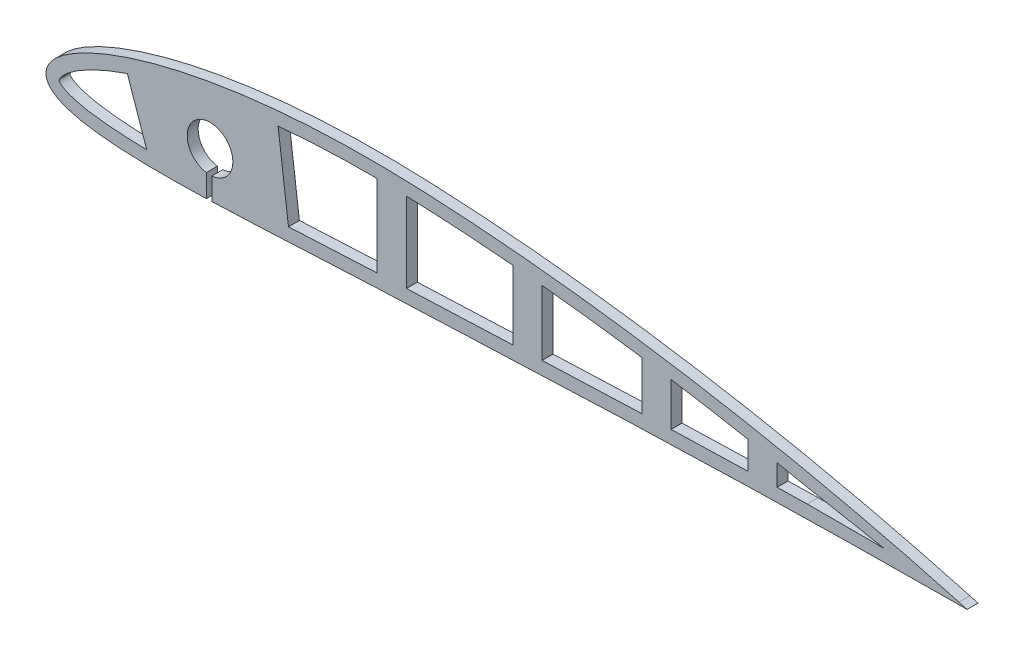
SolidWorks part; units mm, degrees
ref_plane "Front Plane" through (0, 0, 0) normal (0, 0, 1) x (1, 0, 0)
ref_plane "Top Plane" through (0, 0, 0) normal (0, 1, 0) x (1, 0, 0)
ref_plane "Right Plane" through (0, 0, 0) normal (1, 0, 0) x (0, 0, -1)
sketch "Sketch1" plane through (0, 0, 1594.6656) normal (0, 0, 1) x (1, 0, 0)
  line L2 (571.5128, 751.4609) -> (569.2886, 752.0854)
  line L3 (569.2051, 751.4609) -> (571.5128, 751.4609)
  line L4 (569.2051, 751.4609) -> (571.5128, 751.4609) construction
  spline S1 degree 3 poles (569.2886, 752.0854) (569.2078, 752.1078) (568.8853, 752.1974) (568.1605, 752.3973) (566.9556, 752.729) (565.2743, 753.1866) (562.1009, 754.0411) (558.3152, 755.0358) (553.9297, 756.1554) (549.9887, 757.1383) (545.6315, 758.1963) (540.8742, 759.3181) (535.7338, 760.4908) (530.2297, 761.7033) (524.3818, 762.9407) (518.2126, 764.1926) (511.7451, 765.4444) (505.0038, 766.684) (498.015, 767.8998) (490.8053, 769.0779) (483.403, 770.2081) (475.8368, 771.278) (468.1369, 772.277) (460.3337, 773.194) (452.4584, 774.0199) (444.5428, 774.7452) (436.619, 775.3619) (428.7194, 775.8607) (420.844, 776.2435) (413.0149, 776.4797) (405.2648, 776.5088) (397.6615, 776.3435) (390.2476, 775.9856) (383.0567, 775.4408) (376.1212, 774.7193) (369.4725, 773.8315) (363.1401, 772.7913) (357.1519, 771.6135) (351.5339, 770.3153) (346.3098, 768.915) (341.501, 767.4314) (337.1267, 765.8839) (333.2027, 764.2928) (329.7432, 762.6763) (326.7587, 761.0528) (324.2574, 759.4384) (322.2434, 757.8466) (320.7178, 756.2854) (319.6806, 754.7538) (319.1458, 753.2369) (319.159, 751.7555) (319.7158, 750.3843) (320.7825, 749.1883) (322.304, 748.1611) (324.27, 747.2776) (326.6763, 746.5255) (329.5165, 745.9001) (332.7801, 745.3971) (336.4542, 745.0122) (340.5236, 744.7407) (344.9719, 744.5753) (349.7816, 744.5103) (354.9341, 744.5357) (360.4104, 744.6431) (366.1905, 744.8216) (372.2543, 745.0601) (378.5807, 745.3457) (385.1483, 745.6665) (391.935, 746.0089) (398.9183, 746.3597) (406.0748, 746.7054) (413.3888, 747.0362) (420.8688, 747.3274) (428.4856, 747.624) (436.2018, 747.9413) (443.9555, 748.2639) (451.7173, 748.586) (459.4574, 748.9018) (467.146, 749.2057) (474.7531, 749.4935) (482.249, 749.7621) (489.6041, 750.0086) (496.7891, 750.2326) (503.7754, 750.4327) (510.5347, 750.6093) (517.0396, 750.7629) (523.2634, 750.8957) (529.1806, 751.0078) (534.7667, 751.1025) (539.9984, 751.1811) (544.8539, 751.2454) (549.3124, 751.2978) (553.3551, 751.3399) (556.9645, 751.3737) (560.1251, 751.3998) (562.8233, 751.4199) (565.0473, 751.4355) (566.7873, 751.4467) (568.0357, 751.4543) (568.7869, 751.4584) (569.1214, 751.4604) (569.2051, 751.4609) knots 0 0 0 0 0.000491 0.001962 0.004406 0.007815 0.012174 0.023667 0.030754 0.0387 0.04747 0.057032 0.067345 0.07837 0.090062 0.102376 0.115262 0.128669 0.142545 0.156835 0.171482 0.186429 0.201617 0.216985 0.232474 0.248023 0.263569 0.279051 0.29441 0.309776 0.324951 0.339825 0.354342 0.368446 0.382083 0.395202 0.407751 0.419686 0.430962 0.441537 0.451377 0.460447 0.468723 0.476183 0.482815 0.488619 0.49361 0.49783 0.501365 0.504372 0.507113 0.509853 0.512855 0.516368 0.52054 0.525445 0.531118 0.537568 0.544788 0.552762 0.561466 0.570873 0.58095 0.591662 0.602972 0.614841 0.627227 0.640086 0.653377 0.667052 0.681064 0.695367 0.70996 0.724934 0.74004 0.75522 0.770415 0.785568 0.800619 0.81551 0.830182 0.844577 0.858639 0.872311 0.885538 0.898266 0.910444 0.922022 0.932951 0.943187 0.952686 0.961409 0.969318 0.97638 0.982563 0.987842 0.992193 0.995598 0.99804 0.99951 1 1 1 1
  dimension "D1" = 2.2242
  dimension "D2" = 2.3077
  dimension "D3" = 0.6245
extrude "Boss-Extrude1" add sketch "Sketch1" along normal blind 3
sketch "Sketch2" plane through (0, 0, 1597.6656) normal (0, 0, 1) x (1, 0, 0)
  line L1 (527.0417, 758.6959) -> (548.7945, 754.58)
  line L2 (548.7945, 754.58) -> (527.7227, 754.58)
  spline S0 degree 3 poles (1474.0155, 3610.6619) (637.218, 726.0279) (603.832, 742.5568) (568.1605, 752.3973) (566.9556, 752.729) (565.2743, 753.1866) (562.1009, 754.0411) (558.3152, 755.0358) (553.9297, 756.1554) (549.9887, 757.1383) (545.6315, 758.1963) (540.8742, 759.3181) (535.7338, 760.4908) (530.2297, 761.7033) (524.3818, 762.9407) (518.2126, 764.1926) (511.7451, 765.4444) (505.0038, 766.684) (498.015, 767.8998) (490.8053, 769.0779) (483.403, 770.2081) (475.8368, 771.278) (468.1369, 772.277) (460.3337, 773.194) (452.4584, 774.0199) (444.5428, 774.7452) (436.619, 775.3619) (428.7194, 775.8607) (420.844, 776.2435) (413.0149, 776.4797) (405.2648, 776.5088) (397.6615, 776.3435) (390.2476, 775.9856) (383.0567, 775.4408) (376.1212, 774.7193) (369.4725, 773.8315) (363.1401, 772.7913) (357.1519, 771.6135) (351.5339, 770.3153) (346.3098, 768.915) (341.501, 767.4314) (337.1267, 765.8839) (333.2027, 764.2928) (329.7432, 762.6763) (326.7587, 761.0528) (324.2574, 759.4384) (322.2434, 757.8466) (320.7178, 756.2854) (319.6806, 754.7538) (319.1458, 753.2369) (319.159, 751.7555) (319.7158, 750.3843) (320.7825, 749.1883) (322.304, 748.1611) (324.27, 747.2776) (326.6763, 746.5255) (329.5165, 745.9001) (332.7801, 745.3971) (336.4542, 745.0122) (340.5236, 744.7407) (344.9719, 744.5753) (349.7816, 744.5103) (354.9341, 744.5357) (360.4104, 744.6431) (366.1905, 744.8216) (372.2543, 745.0601) (378.5807, 745.3457) (385.1483, 745.6665) (391.935, 746.0089) (398.9183, 746.3597) (406.0748, 746.7054) (413.3888, 747.0362) (420.8688, 747.3274) (428.4856, 747.624) (436.2018, 747.9413) (443.9555, 748.2639) (451.7173, 748.586) (459.4574, 748.9018) (467.146, 749.2057) (474.7531, 749.4935) (482.249, 749.7621) (489.6041, 750.0086) (496.7891, 750.2326) (503.7754, 750.4327) (510.5347, 750.6093) (517.0396, 750.7629) (523.2634, 750.8957) (529.1806, 751.0078) (534.7667, 751.1025) (539.9984, 751.1811) (544.8539, 751.2454) (549.3124, 751.2978) (553.3551, 751.3399) (556.9645, 751.3737) (560.1251, 751.3998) (562.8233, 751.4199) (565.0473, 751.4355) (566.7873, 751.4467) (568.0357, 751.4543) (620.0518, 751.7355) (671.6226, 756.9637) (740.364, -2240.9775) knots -0.212459 -0.212459 -0.212459 -0.212459 0.000491 0.001962 0.004406 0.007815 0.012174 0.023667 0.030754 0.0387 0.04747 0.057032 0.067345 0.07837 0.090062 0.102376 0.115262 0.128669 0.142545 0.156835 0.171482 0.186429 0.201617 0.216985 0.232474 0.248023 0.263569 0.279051 0.29441 0.309776 0.324951 0.339825 0.354342 0.368446 0.382083 0.395202 0.407751 0.419686 0.430962 0.441537 0.451377 0.460447 0.468723 0.476183 0.482815 0.488619 0.49361 0.49783 0.501365 0.504372 0.507113 0.509853 0.512855 0.516368 0.52054 0.525445 0.531118 0.537568 0.544788 0.552762 0.561466 0.570873 0.58095 0.591662 0.602972 0.614841 0.627227 0.640086 0.653377 0.667052 0.681064 0.695367 0.70996 0.724934 0.74004 0.75522 0.770415 0.785568 0.800619 0.81551 0.830182 0.844577 0.858639 0.872311 0.885538 0.898266 0.910444 0.922022 0.932951 0.943187 0.952686 0.961409 0.969318 0.97638 0.982563 0.987842 0.992193 0.995598 0.99804 0.99951 1.300448 1.300448 1.300448 1.300448 only from (569.2886, 752.0854) to (569.2051, 751.4609) construction
  spline S1 degree 3 poles (527.7891, 762.2175) (526.6879, 762.4512) (523.5298, 763.1136) (518.2126, 764.1926) (511.7451, 765.4444) (505.0038, 766.684) (498.015, 767.8998) (490.8053, 769.0779) (483.403, 770.2081) (475.8368, 771.278) (468.1369, 772.277) (460.3337, 773.194) (452.4584, 774.0199) (444.5428, 774.7452) (436.619, 775.3619) (428.7194, 775.8607) (420.844, 776.2435) (413.0149, 776.4797) (405.2648, 776.5088) (397.6615, 776.3435) (390.2476, 775.9856) (383.0567, 775.4408) (376.1212, 774.7193) (369.4725, 773.8315) (363.1401, 772.7913) (357.1519, 771.6135) (351.5339, 770.3153) (346.3098, 768.915) (341.501, 767.4314) (337.1267, 765.8839) (333.2027, 764.2928) (329.7432, 762.6763) (326.7587, 761.0528) (324.2574, 759.4384) (322.2434, 757.8466) (320.7178, 756.2854) (319.6806, 754.7538) (319.1458, 753.2369) (319.159, 751.7555) (319.7158, 750.3843) (320.7825, 749.1883) (322.304, 748.1611) (324.27, 747.2776) (326.6763, 746.5255) (329.5165, 745.9001) (332.7801, 745.3971) (336.4542, 745.0122) (340.5236, 744.7407) (344.9719, 744.5753) (349.7816, 744.5103) (354.9341, 744.5357) (360.4104, 744.6431) (366.1905, 744.8216) (372.2543, 745.0601) (378.5807, 745.3457) (385.1483, 745.6665) (391.935, 746.0089) (398.9183, 746.3597) (406.0748, 746.7054) (413.3888, 747.0362) (420.8688, 747.3274) (428.4856, 747.624) (436.2018, 747.9413) (443.9555, 748.2639) (451.7173, 748.586) (459.4574, 748.9018) (467.146, 749.2057) (474.7531, 749.4935) (482.249, 749.7621) (489.6041, 750.0086) (496.7891, 750.2326) (503.7754, 750.4327) (510.5347, 750.6093) (517.0396, 750.7629) (522.7627, 750.8851) (526.3146, 750.9534) (527.7891, 750.9806) knots 0.083465 0.083465 0.083465 0.083465 0.090062 0.102376 0.115262 0.128669 0.142545 0.156835 0.171482 0.186429 0.201617 0.216985 0.232474 0.248023 0.263569 0.279051 0.29441 0.309776 0.324951 0.339825 0.354342 0.368446 0.382083 0.395202 0.407751 0.419686 0.430962 0.441537 0.451377 0.460447 0.468723 0.476183 0.482815 0.488619 0.49361 0.49783 0.501365 0.504372 0.507113 0.509853 0.512855 0.516368 0.52054 0.525445 0.531118 0.537568 0.544788 0.552762 0.561466 0.570873 0.58095 0.591662 0.602972 0.614841 0.627227 0.640086 0.653377 0.667052 0.681064 0.695367 0.70996 0.724934 0.74004 0.75522 0.770415 0.785568 0.800619 0.81551 0.830182 0.844577 0.858639 0.872311 0.885538 0.898266 0.910444 0.919086 0.919086 0.919086 0.919086
  spline S2 degree 1 poles (527.0417, 758.6959) (527.7227, 754.58) knots 0 0 1 1 construction
  spline S3 degree 3 poles (527.0417, 758.6959) (518.3683, 760.5366) (500.951, 763.8997) (474.6628, 767.966) (452.6455, 770.4843) (434.9947, 771.8985) (421.7276, 772.6482) (408.5168, 772.9897) (395.3109, 772.7186) (382.1513, 771.8268) (369.0794, 770.2343) (358.3167, 768.246) (349.847, 766.1775) (343.5957, 764.3541) (338.5068, 762.5685) (334.5578, 760.9433) (331.6806, 759.611) (328.9259, 758.1483) (326.7893, 756.8009) (325.2575, 755.6451) (324.2356, 754.7445) (323.4068, 753.8367) (322.9706, 753.1632) (322.806, 752.7516) (322.772, 752.5946) (322.7737, 752.4904) (322.7757, 752.4752) (322.8114, 752.3798) (322.9212, 752.2073) (323.3921, 751.7489) (324.3594, 751.1809) (325.9668, 750.4938) (328.321, 749.8167) (331.3568, 749.2376) (334.5038, 748.823) (337.7102, 748.531) (342.0359, 748.266) (347.4998, 748.1146) (354.1019, 748.1186) (360.7281, 748.2487) (369.5843, 748.5376) (380.6814, 749.0417) (394.0264, 749.7204) (407.3902, 750.3878) (420.7874, 750.9298) (434.1212, 751.4525) (451.9322, 752.2032) (474.2053, 753.1053) (500.9583, 753.9965) (518.8009, 754.4154) (527.7227, 754.58) knots 0.083465 0.083465 0.083465 0.083465 0.135691 0.187918 0.240144 0.266257 0.29237 0.318483 0.344597 0.37071 0.396823 0.422936 0.435993 0.449049 0.462106 0.468634 0.475163 0.481691 0.488219 0.491483 0.494747 0.498012 0.501276 0.502908 0.50454 0.506172 0.507804 0.509436 0.511068 0.514332 0.517596 0.520861 0.527389 0.533917 0.540445 0.546974 0.553502 0.566559 0.579615 0.592672 0.605728 0.631842 0.657955 0.684068 0.710181 0.736294 0.762407 0.814634 0.86686 0.919086 0.919086 0.919086 0.919086
  dimension "D2" = 20.4106
  dimension "D3" = 41.416
  dimension "D1" = 3.6
extrude "Cut-Extrude1" cut sketch "Sketch2" against normal blind 10 contours L1 S3 L2
sketch "Sketch3" plane through (0, 0, 1597.6656) normal (0, 0, 1) x (1, 0, 0)
  line L0 (341.459, 763.5841) -> (346.7502, 748.157)
  line L1 (349.1123, 765.9288) -> (355.2092, 748.1525)
  line L2 (374.8049, 770.8978) -> (377.5857, 748.907)
  line L3 (382.7589, 771.7654) -> (385.6004, 749.2948)
  line L4 (409.9199, 772.8805) -> (409.9199, 750.4788)
  line L5 (417.9199, 772.7198) -> (417.9199, 750.8122)
  line L6 (447.0835, 770.8916) -> (447.0835, 751.9966)
  line L7 (455.0835, 770.1204) -> (455.0835, 752.3265)
  line L8 (482.4324, 766.6979) -> (482.4324, 753.3674)
  line L9 (490.4324, 765.4793) -> (490.4324, 753.6341)
  line L10 (511.4605, 761.8237) -> (511.4605, 754.2305)
  line L11 (519.4605, 760.2624) -> (519.4605, 754.4148)
  spline S0 degree 3 poles (-11417.7675, -27.8816) (2199.8699, -1917.6866) (1537.1945, 603.6136) (474.6628, 767.966) (452.6455, 770.4843) (434.9947, 771.8985) (421.7276, 772.6482) (408.5168, 772.9897) (395.3109, 772.7186) (382.1513, 771.8268) (369.0794, 770.2343) (358.3167, 768.246) (349.847, 766.1775) (343.5957, 764.3541) (338.5068, 762.5685) (334.5578, 760.9433) (331.6806, 759.611) (328.9259, 758.1483) (326.7893, 756.8009) (325.2575, 755.6451) (324.2356, 754.7445) (323.4068, 753.8367) (322.9706, 753.1632) (322.806, 752.7516) (322.772, 752.5946) (322.7737, 752.4904) (322.7757, 752.4752) (322.8114, 752.3798) (322.9212, 752.2073) (323.3921, 751.7489) (324.3594, 751.1809) (325.9668, 750.4938) (328.321, 749.8167) (331.3568, 749.2376) (334.5038, 748.823) (337.7102, 748.531) (342.0359, 748.266) (347.4998, 748.1146) (354.1019, 748.1186) (360.7281, 748.2487) (369.5843, 748.5376) (380.6814, 749.0417) (394.0264, 749.7204) (407.3902, 750.3878) (420.7874, 750.9298) (434.1212, 751.4525) (451.9322, 752.2032) (474.2053, 753.1053) (2123.5149, 808.0517) (3825.2982, -620.0168) (-2516.8948, -10259.5003) knots -6.092595 -6.092595 -6.092595 -6.092595 0.135691 0.187918 0.240144 0.266257 0.29237 0.318483 0.344597 0.37071 0.396823 0.422936 0.435993 0.449049 0.462106 0.468634 0.475163 0.481691 0.488219 0.491483 0.494747 0.498012 0.501276 0.502908 0.50454 0.506172 0.507804 0.509436 0.511068 0.514332 0.517596 0.520861 0.527389 0.533917 0.540445 0.546974 0.553502 0.566559 0.579615 0.592672 0.605728 0.631842 0.657955 0.684068 0.710181 0.736294 0.762407 0.814634 0.86686 10.421587 10.421587 10.421587 10.421587 only from (527.0417, 758.6959) to (527.7227, 754.58) construction
  spline S1 degree 3 poles (519.4605, 760.2624) (516.7968, 760.7979) (514.1301, 761.3184) (511.4605, 761.8237) knots 0.098664 0.098664 0.098664 0.098664 0.114666 0.114666 0.114666 0.114666
  spline S2 degree 3 poles (346.7502, 748.157) (347.0025, 748.1528) (349.4472, 748.1158) (352.2682, 748.1175) (354.8414, 748.1477) (355.2092, 748.1525) knots 0.565055 0.565055 0.565055 0.565055 0.566559 0.579615 0.581793 0.581793 0.581793 0.581793
  spline S3 degree 3 poles (349.1123, 765.9288) (347.2661, 765.4238) (344.7027, 764.6672) (342.1758, 763.8299) (341.459, 763.5841) knots 0.437551 0.437551 0.437551 0.437551 0.449049 0.453635 0.453635 0.453635 0.453635
  spline S4 degree 3 poles (377.5857, 748.907) (378.6189, 748.9551) (381.2895, 749.082) (383.9617, 749.2133) (385.6004, 749.2948) knots 0.625767 0.625767 0.625767 0.625767 0.631842 0.641464 0.641464 0.641464 0.641464
  spline S5 degree 3 poles (382.7589, 771.7654) (382.5612, 771.7472) (379.9042, 771.4988) (377.2526, 771.2073) (374.8049, 770.8978) knots 0.369529 0.369529 0.369529 0.369529 0.37071 0.385397 0.385397 0.385397 0.385397
  spline S6 degree 3 poles (409.9199, 750.4788) (412.5868, 750.5949) (415.2546, 750.7048) (417.9199, 750.8122) knots 0.688993 0.688993 0.688993 0.688993 0.704602 0.704602 0.704602 0.704602
  spline S7 degree 3 poles (417.9199, 772.7198) (415.2513, 772.8044) (412.5853, 772.8605) (409.9199, 772.8805) knots 0.299904 0.299904 0.299904 0.299904 0.315711 0.315711 0.315711 0.315711
  spline S8 degree 3 poles (447.0835, 751.9966) (447.2157, 752.0021) (449.8821, 752.1131) (452.5488, 752.2232) (455.0835, 752.3265) knots 0.761632 0.761632 0.761632 0.761632 0.762407 0.777268 0.777268 0.777268 0.777268
  spline S9 degree 3 poles (455.0835, 770.1204) (452.7998, 770.356) (450.1333, 770.6159) (447.4656, 770.8574) (447.0835, 770.8916) knots 0.22661 0.22661 0.22661 0.22661 0.240144 0.242406 0.242406 0.242406 0.242406
  spline S10 degree 3 poles (482.4324, 753.3674) (485.0988, 753.4596) (487.7654, 753.5486) (490.4324, 753.6341) knots 0.830692 0.830692 0.830692 0.830692 0.846311 0.846311 0.846311 0.846311
  spline S11 degree 3 poles (490.4324, 765.4793) (487.768, 765.9011) (485.1013, 766.3074) (482.4324, 766.6979) knots 0.156574 0.156574 0.156574 0.156574 0.172465 0.172465 0.172465 0.172465
  spline S12 degree 3 poles (511.4605, 754.2305) (514.127, 754.2959) (516.7937, 754.3573) (519.4605, 754.4148) knots 0.887353 0.887353 0.887353 0.887353 0.902964 0.902964 0.902964 0.902964
  spline M8 degree 3 poles (527.7227, 754.58) (518.8009, 754.4154) (500.9583, 753.9965) (474.2053, 753.1053) (451.9322, 752.2032) (434.1212, 751.4525) (420.7874, 750.9298) (407.3902, 750.3878) (394.0264, 749.7204) (380.6814, 749.0417) (369.5843, 748.5376) (360.7281, 748.2487) (354.1019, 748.1186) (347.4998, 748.1146) (342.0359, 748.266) (337.7102, 748.531) (334.5038, 748.823) (331.3568, 749.2376) (328.321, 749.8167) (325.9668, 750.4938) (324.3594, 751.1809) (323.3921, 751.7489) (322.9212, 752.2073) (322.8114, 752.3798) (322.7757, 752.4752) (322.7737, 752.4904) (322.772, 752.5946) (322.806, 752.7516) (322.9706, 753.1632) (323.4068, 753.8367) (324.2356, 754.7445) (325.2575, 755.6451) (326.7893, 756.8009) (328.9259, 758.1483) (331.6806, 759.611) (334.5578, 760.9433) (338.5068, 762.5685) (343.5957, 764.3541) (349.847, 766.1775) (358.3167, 768.246) (369.0794, 770.2343) (382.1513, 771.8268) (395.3109, 772.7186) (408.5168, 772.9897) (421.7276, 772.6482) (434.9947, 771.8985) (452.6455, 770.4843) (474.6628, 767.966) (500.951, 763.8997) (518.3683, 760.5366) (527.0417, 758.6959) knots 0.083465 0.083465 0.083465 0.083465 0.135691 0.187918 0.240144 0.266257 0.29237 0.318483 0.344597 0.37071 0.396823 0.40988 0.422936 0.435993 0.449049 0.455578 0.462106 0.468634 0.475163 0.481691 0.484955 0.488219 0.491483 0.493115 0.494747 0.496379 0.498012 0.499644 0.501276 0.50454 0.507804 0.511068 0.514332 0.520861 0.527389 0.533917 0.540445 0.553502 0.566559 0.579615 0.605728 0.631842 0.657955 0.684068 0.710181 0.736294 0.762407 0.814634 0.86686 0.919086 0.919086 0.919086 0.919086
  dimension "D1" = 8
  dimension "D2" = 8
  dimension "D3" = 8
  dimension "D4" = 8
  dimension "D5" = 8
  dimension "D6" = 8
  dimension "D7" = 49.7446
  dimension "D8" = 78.7727
  dimension "D9" = 114.1216
  dimension "D10" = 151.2852
  dimension "D11" = 183.6047
  dimension "D12" = 186.4462
  dimension "D13" = 213.9958
  dimension "D14" = 220.0927
extrude "Boss-Extrude2" add sketch "Sketch3" against normal blind 3 contours L3 L2 M8 | L5 L4 M8 | L7 L6 M8 | L9 L8 M8 | L11 L10 M8 | L1 S2 L0 S3
sketch "Sketch6" plane through (0, 0, 1597.6656) normal (0, 0, 1) x (1, 0, 0)
  line L0 (374.8049, 770.8978) -> (377.5857, 748.907) construction
  line L1 (349.1123, 765.9288) -> (355.2092, 748.1525) construction
  line L2 (374.8049, 770.8978) -> (377.5857, 748.907)
  line L3 (349.1123, 765.9288) -> (355.2092, 748.1525)
  spline S0 degree 3 poles (333.6007, 2733.1507) (84.3449, 801.7786) (218.9277, 743.6234) (558.9603, 754.7148) (768.9696, 835.8348) (789.9826, -1176.5624) knots -0.256597 -0.256597 -0.256597 -0.256597 0.592672 0.605728 1.748613 1.748613 1.748613 1.748613 only from (355.2092, 748.1525) to (377.5857, 748.907) construction
  spline S1 degree 3 poles (-732.3663, 2423.0354) (943.7378, 420.7004) (608.7038, 814.5015) (358.3167, 768.246) (237.3844, 738.7104) (171.7517, 572.5227) (1313.3888, -972.0185) knots -1.08277 -1.08277 -1.08277 -1.08277 0.396823 0.422936 0.435993 1.142528 1.142528 1.142528 1.142528 only from (374.8049, 770.8978) to (349.1123, 765.9288) construction
  spline S2 degree 3 poles (355.2092, 748.1525) (357.0474, 748.1768) (361.0973, 748.2607) (368.5542, 748.504) (374.1777, 748.7483) (377.5857, 748.907) knots 0.581793 0.581793 0.581793 0.581793 0.592672 0.605728 0.625767 0.625767 0.625767 0.625767
  spline S3 degree 3 poles (374.8049, 770.8978) (372.9007, 770.657) (366.658, 769.787) (358.3167, 768.246) (351.7117, 766.6329) (349.3626, 765.9972) (349.1123, 765.9288) knots 0.385397 0.385397 0.385397 0.385397 0.396823 0.422936 0.435993 0.437551 0.437551 0.437551 0.437551
extrude "Boss-Extrude3" add sketch "Sketch6" against normal blind 3
sketch "Sketch5" plane through (0, 0, 1597.6656) normal (0, 0, 1) x (1, 0, 0)
  line L0 (455.0835, 770.1204) -> (455.0835, 752.3265) construction
  line L2 (548.7945, 754.58) -> (527.7227, 754.58) construction
  circle A0 centre (364.1123, 757.08) radius 6.25
  dimension "D2" = 12.5
  dimension "D1" = 90.9712
  dimension "D3" = 2.5
extrude "Cut-Extrude2" cut sketch "Sketch5" against normal blind 3 contours A0
sketch "Sketch9" plane through (0, 0, 1597.6656) normal (0, 0, 1) x (1, 0, 0)
  line L1 (363.1123, 754.2254) -> (364.6123, 754.2254)
  line L2 (363.1123, 754.2254) -> (363.1123, 743.1792)
  line L3 (363.1123, 743.1792) -> (364.6123, 743.1792)
  line L4 (364.6123, 754.2254) -> (364.6123, 743.1792)
  circle A0 centre (364.1123, 757.08) radius 6.25 construction
  dimension "D1" = 1.5
  dimension "D2" = 0.5
extrude "Cut-Extrude3" cut sketch "Sketch9" against normal blind 3
